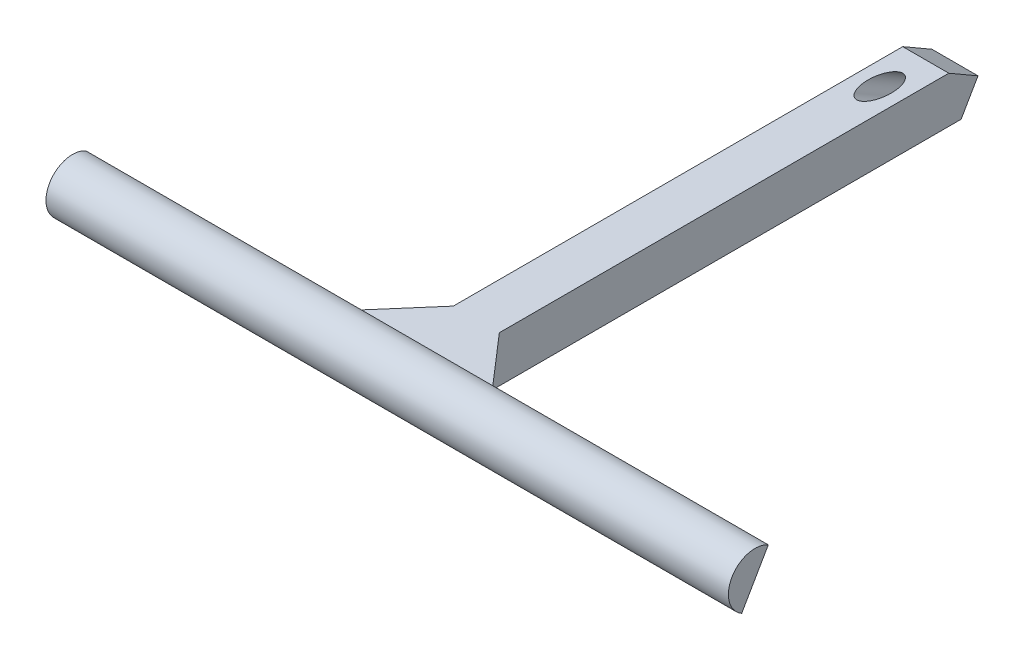
SolidWorks part; units mm, degrees
ref_plane "前视基准面" through (0, 0, 0) normal (0, 0, 1) x (1, 0, 0)
ref_plane "上视基准面" through (0, 0, 0) normal (0, 1, 0) x (1, 0, 0)
ref_plane "右视基准面" through (0, 0, 0) normal (1, 0, 0) x (0, 0, -1)
sketch "草图1" plane through (0, 0, 0) normal (0, 1, 0) x (1, 0, 0)
  line L1 (2.7, -32.5) -> (-2.7, -32.5)
  line L2 (2.7, -32.5) -> (2.7, 32.5)
  line L3 (2.7, 32.5) -> (-2.7, 32.5)
  line L4 (-2.7, -32.5) -> (-2.7, 32.5)
  line L5 (2.7, -32.5) -> (-2.7, 32.5) construction
  line L6 (2.7, 32.5) -> (-2.7, -32.5) construction
  point P0 (0, 0)
  point P6 (0, -24)
  dimension "D1" = 5.4
  dimension "D2" = 65
extrude "凸台-拉伸1" add sketch "草图1" along normal mid plane 5.4
sketch "草图3" plane through (0, 0, 0) normal (1, 0, 0) x (0, 0, -1)
  line L0 (32.5, 0.7235) -> (29.0765, 2.7)
  line L2 (-32.5, 2.7) -> (32.5, 2.7) construction
  line L3 (29.0765, 2.7) -> (27.1, -0.7235)
  line L4 (27.1, -0.7235) -> (30.5235, -2.7)
  line L5 (-32.5, -2.7) -> (32.5, -2.7) construction
  line L6 (30.5235, -2.7) -> (32.5, 0.7235)
  line L7 (29.0765, 2.7) -> (32.5, 2.7)
  line L8 (32.5, 2.7) -> (32.5, -2.7)
  line L9 (32.5, -2.7) -> (30.5235, -2.7)
  line L10 (32.5, -2.7) -> (30.5235, -2.7)
  line L11 (29.0765, 2.7) -> (32.5, 2.7)
  dimension "D1" = 30
extrude "切除-拉伸1" cut sketch "草图3" against normal through all both and the other way through all contours L8 L7 L0 | L9 L8 L6
sketch "草图4" plane through (0, 0, 0) normal (1, 0, 0) x (0, 0, -1)
  line L0 (-32.5, -2.7) -> (-29.3823, 2.7)
  line L1 (30.5235, -2.7) -> (32.5, 0.7235) construction
  circle A0 centre (-30.9412, 0) radius 3.1177
extrude "凸台-拉伸2" add sketch "草图4" along normal mid plane 80 contours L0 A0
chamfer "倒角1" distance 5 angle 45 2 edges at (-2.7, 0, 30.9412) (2.7, 0, 30.9412)
sketch "草图6" plane through (0, -13.892, -24.0617) normal (0, -0.5, -0.866) x (-1, 0, 0)
  line L0 (2.7, 12.9235) -> (2.7, 16.8765) construction
  line L2 (2.7, 16.8765) -> (-2.7, 16.8765) construction
  circle A0 centre (0, 14.1765) radius 1.35
  dimension "D1" = 2.7
  dimension "D2" = 2.7
  dimension "D3" = 2.7
extrude "切除-拉伸2" cut sketch "草图6" against normal through all both and the other way through all
